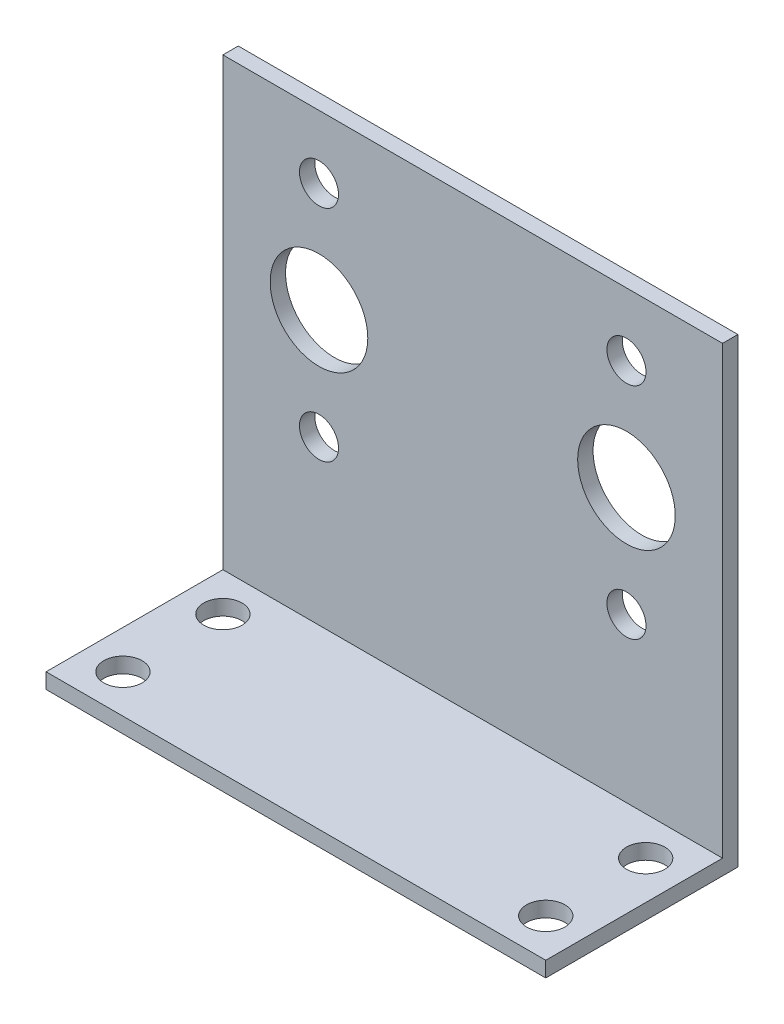
SolidWorks part; units mm, degrees
ref_plane "Front Plane" through (0, 0, 0) normal (0, 0, 1) x (1, 0, 0)
ref_plane "Top Plane" through (0, 0, 0) normal (0, 1, 0) x (1, 0, 0)
ref_plane "Right Plane" through (0, 0, 0) normal (1, 0, 0) x (0, 0, -1)
sketch "Sketch1" plane through (0, 0, 0) normal (0, 0, 1) x (1, 0, 0)
  line L1 (65, 60) -> (-65, 60)
  line L2 (65, 60) -> (65, -60)
  line L3 (65, -60) -> (-65, -60)
  line L4 (-65, 60) -> (-65, -60)
  line L5 (65, 60) -> (-65, -60) construction
  line L6 (65, -60) -> (-65, 60) construction
  point P0 (0, 0)
  dimension "D1" = 120
  dimension "D2" = 130
extrude "Boss-Extrude1" add sketch "Sketch1" along normal blind 4
sketch "Sketch2" plane through (0, 0, 4) normal (0, 0, 1) x (1, 0, 0)
  line L0 (0, 60) -> (0, -60) construction
  line L1 (65, 60) -> (-65, 60) construction
  line L2 (-65, -60) -> (65, -60) construction
  line L3 (-65, 15) -> (65, 15) construction
  line L4 (-65, 60) -> (-65, -60) construction
  line L5 (65, -60) -> (65, 60) construction
  line L6 (-40, 60) -> (-40, -60) construction
  circle A0 centre (-40, 15) radius 12.7
  circle A1 centre (-40, 43.575) radius 5.08
  circle A2 centre (-40, -13.575) radius 5.08
  circle A3 centre (40, -13.575) radius 5.08
  circle A4 centre (40, 15) radius 12.7
  circle A5 centre (40, 43.575) radius 5.08
  dimension "D3" = 25.4
  dimension "D5" = 10.16
  dimension "D1" = 75
  dimension "D2" = 40
  dimension "D4" = 28.575
extrude "Cut-Extrude1" cut sketch "Sketch2" against normal through all
sketch "Sketch3" plane through (0, 0, 4) normal (0, 0, 1) x (1, 0, 0)
  line L0 (65, -60) -> (65, 60) construction
  line L1 (-65, -60) -> (65, -60)
  line L2 (-65, -60) -> (-65, -56)
  line L3 (-65, -56) -> (65, -56)
  line L4 (65, -60) -> (65, -56)
  dimension "D1" = 4
extrude "Boss-Extrude2" add sketch "Sketch3" along normal blind 50 from surface at -4 contours L3 L4 L1 L2 starting at face at (-34.92, 43.575, 0)
sketch "Sketch5" plane through (0, -56, 0) normal (0, 1, 0) x (1, 0, 0)
  line L0 (-55, -4) -> (-55, -65.231) construction
  line L1 (65, -4) -> (-65, -4) construction
  line L2 (-65, -50) -> (-65, -4) construction
  line L3 (65, -50) -> (-65, -50) construction
  line L4 (65, -4) -> (-65, -4) construction
  line L5 (0, 0) -> (0, -65.231) construction
  circle A0 centre (-55, -14) radius 5
  circle A1 centre (-55, -40) radius 5
  dimension "D1" = 10
  dimension "D2" = 10
  dimension "D3" = 10
  dimension "D4" = 10
  dimension "D5" = 10
  dimension "D6" = 55
  dimension "D7" = 26
extrude "Cut-Extrude2" cut sketch "Sketch5" against normal through all
mirror "Mirror1" about plane through (0, 0, 0) normal (1, 0, 0) of "Cut-Extrude2"
